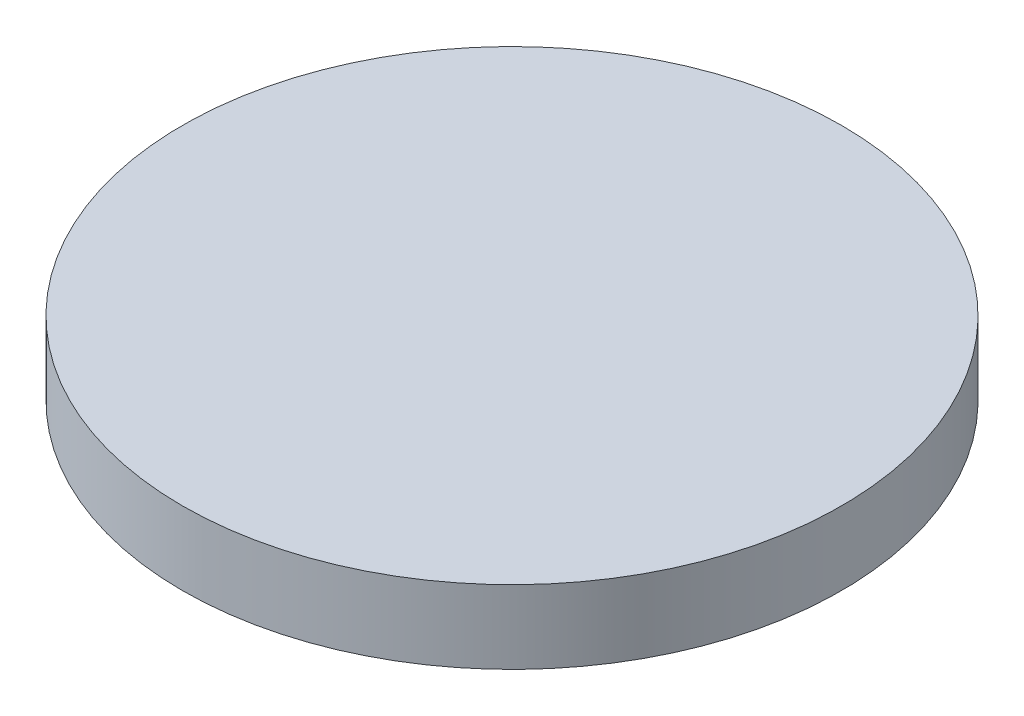
SolidWorks part; units mm, degrees
ref_plane "Alzado" through (0, 0, 0) normal (0, 0, 1) x (1, 0, 0)
ref_plane "Planta" through (0, 0, 0) normal (0, 1, 0) x (1, 0, 0)
ref_plane "Vista lateral" through (0, 0, 0) normal (1, 0, 0) x (0, 0, -1)
sketch "Croquis1" plane through (0, 0, 0) normal (0, 1, 0) x (1, 0, 0)
  circle A0 centre (0, 0) radius 44.9
  dimension "D1" = 89.8
extrude "Saliente-Extruir1" add sketch "Croquis1" along normal blind 10
